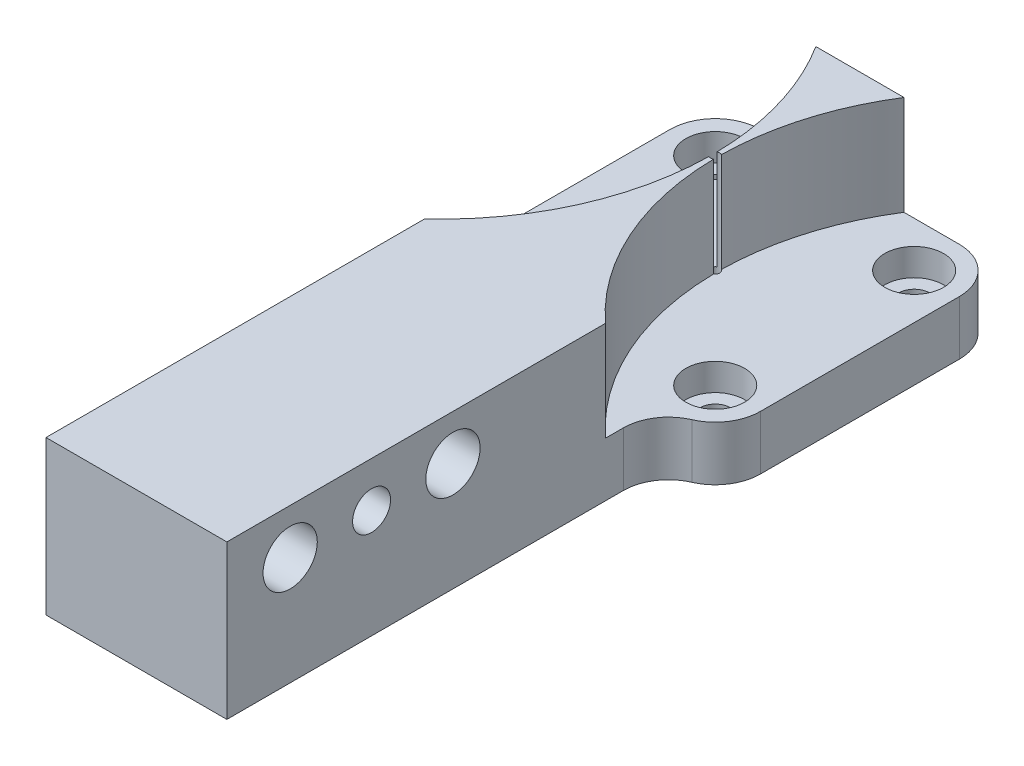
SolidWorks part; units mm, degrees
ref_plane "Front Plane" through (0, 0, 0) normal (0, 0, 1) x (1, 0, 0)
ref_plane "Top Plane" through (0, 0, 0) normal (0, 1, 0) x (1, 0, 0)
ref_plane "Right Plane" through (0, 0, 0) normal (1, 0, 0) x (0, 0, -1)
sketch "Sketch1" plane through (0, 0, 0) normal (0, 1, 0) x (1, 0, 0)
  line L0 (-16.25, 0) -> (16.25, 0)
  line L1 (-16.25, 0) -> (-16.25, -80.25)
  line L2 (-16.25, -80.25) -> (16.25, -80.25)
  line L3 (16.25, -80.25) -> (16.25, 0)
  line L4 (-0.45, -16.25) -> (-0.25, -16.25) construction
  line L5 (0.45, -16.25) -> (0.25, -16.25) construction
  line L6 (-16.25, -52.25) -> (16.25, -52.25) construction
  line L7 (11, -27.25) -> (-11, -27.25) construction
  line L8 (11, -27.25) -> (11, -5.25) construction
  line L9 (11, -5.25) -> (-11, -5.25) construction
  line L10 (-11, -27.25) -> (-11, -5.25) construction
  line L11 (11, -27.25) -> (-11, -5.25) construction
  line L12 (11, -5.25) -> (-11, -27.25) construction
  line L13 (-16.25, -58.25) -> (16.25, -58.25) construction
  line L14 (-16.25, -76.25) -> (16.25, -76.25) construction
  line L15 (-16.25, -70.25) -> (16.25, -70.25) construction
  line L16 (-16.25, -66.75) -> (16.25, -66.75) construction
  line L17 (-16.25, -61.75) -> (16.25, -61.75) construction
  line L18 (0, -52.25) -> (0, -58.25) construction
  line L19 (0, -66.75) -> (0, -61.75) construction
  line L20 (0, -70.25) -> (0, -76.25) construction
  line L21 (0, -58.25) -> (0, -66.75) construction
  line L22 (0, -61.75) -> (0, -70.25) construction
  line L23 (-16.25, -48.25) -> (16.25, -48.25) construction
  line L24 (0, -52.25) -> (0, -48.25) construction
  line L25 (0, -76.25) -> (0, -80.25) construction
  line L26 (0, -16.25) -> (0, 15.25) construction
  line L27 (-12.775, 15.25) -> (12.775, 15.25) construction
  line L28 (-30.25, -46.25) -> (-30.25, -48.25) construction
  arc A0 (-16.25, -42.783) -> (-5.0322, 0) centre (-30.25, -16.25) ccw construction
  circle A1 centre (0, -16.25) radius 0.45 construction
  arc A2 (5.0322, 0) -> (16.25, -42.783) centre (30.25, -16.25) ccw construction
  circle A3 centre (-11, -5.25) radius 5.25 construction
  circle A4 centre (-11, -5.25) radius 3.25 construction
  circle A5 centre (-11, -5.25) radius 1.5 construction
  arc A6 (-16.25, -42.783) -> (-5.0322, 0) centre (-30.25, -16.25) cw construction
  circle A7 centre (-12.775, 15.25) radius 5 construction
  circle A8 centre (12.775, 15.25) radius 5 construction
  point P43 (0, -55.25)
  point P44 (0, -73.25)
  dimension "D1" = 0.9
  dimension "D4" = 2
  dimension "D5" = 6.5
  dimension "D6" = 3
  dimension "D7" = 30
  dimension "D17" = 10
  dimension "D2" = 0.2
  dimension "D3" = 22
  dimension "D8" = 32.5
  dimension "D9" = 4
  dimension "D10" = 6
  dimension "D11" = 18
  dimension "D12" = 5
  dimension "D13" = 2
  dimension "D15" = 31.5
  dimension "D16" = 25.55
  dimension "D18" = 3.5
extrude "Boss-Extrude1" add sketch "Sketch1" against normal blind 6
sketch "Sketch2" plane through (0, 0, 0) normal (0, 1, 0) x (1, 0, 0)
  line L0 (-5.0322, 0) -> (5.0322, 0)
  line L1 (-16.25, -42.783) -> (-16.25, -80.25)
  line L2 (-16.25, -80.25) -> (16.25, -80.25)
  line L3 (16.25, -80.25) -> (16.25, -42.783)
  arc A0 (5.0322, 0) -> (16.25, -42.783) centre (30.25, -16.25) ccw construction
  arc A1 (-16.25, -42.783) -> (-5.0322, 0) centre (-30.25, -16.25) ccw construction
  arc A2 (5.0322, 0) -> (16.25, -42.783) centre (30.25, -16.25) ccw
  arc A3 (-16.25, -42.783) -> (-5.0322, 0) centre (-30.25, -16.25) ccw
extrude "Boss-Extrude2" add sketch "Sketch2" along normal blind 11
sketch "Sketch3" plane through (16.25, 0, 0) normal (1, 0, 0) x (0, 0, -1)
  line L0 (-73.25, 11) -> (-73.25, 1) construction
  line L1 (-80.25, 11) -> (-42.783, 11) construction
  line L3 (-55.25, 11) -> (-55.25, 1) construction
  line L4 (-64.25, 11) -> (-64.25, 1) construction
  line L6 (-80.25, 0) -> (0, 0) construction
  line L7 (-66.75, 0) -> (-61.75, 0) construction
  point P20 (-64.25, 0)
  dimension "D1" = 10
hole_wizard "Ø6.0mm Dowel Hole1" positions "Sketch4" profile "Sketch5" hole size "Ø6.0" standard "ANSI Metric" end condition through all
sketch "Sketch4" plane through (16.25, 0, 0) normal (1, 0, 0) x (0, 0, -1)
  line L0 (-73.25, 11) -> (-73.25, 1) construction
  line L1 (-55.25, 11) -> (-55.25, 1) construction
  point P0 (-73.25, 6)
  point P4 (-55.25, 6)
sketch "Sketch5" plane through (16.25, 6, 73.25) normal (0, 1, 0) x (0, 0, -1)
  line L0 (0, 0) -> (0, 32.5)
  line L1 (0, 32.5) -> (3, 32.5)
  line L2 (3, 32.5) -> (3, 0)
  line L5 (3, 0) -> (0, 0)
  line L11 (0, -6.35) -> (0, 107.95) construction
  dimension "Thru Hole Dia." = 6
  dimension "Thru Hole Depth" = 32.5
hole_wizard "M5x0.8 Tapped Hole1" positions "Sketch6" profile "Sketch7" tap size "M5x0.8" standard "ANSI Metric" end condition through all
sketch "Sketch6" plane through (16.25, 0, 0) normal (1, 0, 0) x (0, 0, -1)
  line L0 (-64.25, 11) -> (-64.25, 1) construction
  point P0 (-64.25, 6)
sketch "Sketch7" plane through (16.25, 6, 64.25) normal (0, 1, 0) x (0, 0, -1)
  line L0 (0, 0) -> (0, 32.5)
  line L1 (0, 32.5) -> (2.1, 32.5)
  line L2 (2.1, 32.5) -> (2.1, 0)
  line L5 (2.1, 0) -> (0, 0)
  line L11 (0, -6.35) -> (0, 107.95) construction
  dimension "Thru Tap Drill Dia." = 4.2
  dimension "Thru Tap Drill Depth" = 32.5
cosmetic thread "Hole Thread1" parameters "D2"=5
hole_wizard "CBORE for M3 SHCS1" positions "Sketch8" profile "Sketch9" counterbore size "M3" standard "ANSI Metric" end condition through all
sketch "Sketch8" plane through (0, 0, 0) normal (0, 1, 0) x (1, 0, 0)
  point P0 (-11, -5.25)
  point P3 (11, -5.25)
  point P6 (11, -27.25)
  point P9 (-11, -27.25)
sketch "Sketch9" plane through (-11, 0, 5.25) normal (1, 0, 0) x (0, 0, 1)
  line L0 (0, 0) -> (0, 6)
  line L1 (0, 6) -> (1.7, 6)
  line L3 (1.7, 6) -> (1.7, 3)
  line L4 (1.7, 3) -> (3.25, 3)
  line L5 (3.25, 3) -> (3.25, 0)
  line L7 (3.25, 0) -> (0, 0)
  line L11 (0, -6.35) -> (0, 107.95) construction
  dimension "Thru Hole Dia." = 3.4
  dimension "Thru Hole Depth" = 6
  dimension "C'Bore Dia." = 6.5
  dimension "C'Bore Depth" = 3
hole_wizard "Ø1.0 (1) Diameter Hole1" positions "Sketch10" profile "Sketch11" hole size "Ø1.0" standard "ANSI Metric" end condition through all
sketch "Sketch10" plane through (0, 11, 0) normal (0, 1, 0) x (1, 0, 0)
  point P0 (0, -16.25)
sketch "Sketch11" plane through (0, 11, 16.25) normal (1, 0, 0) x (0, 0, 1)
  line L0 (0, 0) -> (0, 17)
  line L1 (0, 17) -> (0.5, 17)
  line L2 (0.5, 17) -> (0.5, 0)
  line L5 (0.5, 0) -> (0, 0)
  line L11 (0, -6.35) -> (0, 107.95) construction
  dimension "Thru Hole Dia." = 1
  dimension "Thru Hole Depth" = 17
sketch "Sketch12" plane through (0, -6, 0) normal (0, -1, 0) x (1, 0, 0)
  circle A0 centre (0, 16.25) radius 1.5
  dimension "D1" = 3
extrude "Cut-Extrude1" cut sketch "Sketch12" against normal blind 5
sketch "Sketch13" plane through (0, 11, 0) normal (0, 1, 0) x (1, 0, 0)
  line L0 (-16.25, 0) -> (-16.25, -80.25) construction
  line L1 (-16.25, -45.25) -> (-10.25, -45.25)
  line L2 (-16.25, -45.25) -> (-16.25, -80.25)
  line L3 (-16.25, -80.25) -> (-10.25, -80.25)
  line L4 (-10.25, -45.25) -> (-10.25, -80.25)
  line L5 (-16.25, -80.25) -> (16.25, -80.25) construction
  line L6 (16.25, -80.25) -> (16.25, 0) construction
  line L7 (16.25, -45.25) -> (10.25, -45.25)
  line L8 (16.25, -45.25) -> (16.25, -80.25)
  line L9 (16.25, -80.25) -> (10.25, -80.25)
  line L10 (10.25, -45.25) -> (10.25, -80.25)
  line L11 (-16.25, -48.25) -> (16.25, -48.25) construction
  arc A0 (-16.25, -42.783) -> (-0.2531, -16.6812) centre (-30.25, -16.25) ccw construction
  point P16 (-30.25, -16.25)
  dimension "D1" = 3
  dimension "D2" = 20
extrude "Cut-Extrude2" cut sketch "Sketch13" against normal through all
fillet "Fillet1" radius 2.3813 2 edges at (10.25, 2.5, 45.25) (-10.25, 2.5, 45.25)
sketch "Sketch14" plane through (0, 11, 0) normal (0, 1, 0) x (1, 0, 0)
  line L0 (5.0322, 0) -> (-5.0322, 0) construction
  line L1 (-17.25, 1) -> (17.25, 1)
  line L2 (-17.25, 1) -> (-17.25, -81.25)
  line L3 (-17.25, -81.25) -> (17.25, -81.25)
  line L4 (17.25, 1) -> (17.25, -81.25)
  line L5 (-10, -80.25) -> (-10, -36.4152)
  line L6 (-10.25, -80.25) -> (10.25, -80.25) construction
  line L7 (-10, -80.25) -> (10, -80.25)
  line L8 (10, -80.25) -> (10, -36.4152)
  line L9 (-16, -5.25) -> (-16, -27.25)
  line L10 (-11, -0.25) -> (11, -0.25)
  line L11 (16, -5.25) -> (16, -27.25)
  arc A0 (-11, -0.25) -> (-16, -5.25) centre (-11, -5.25) ccw
  circle A2 centre (-16.25, 0) radius 1 construction
  circle A3 centre (-10.25, -80.25) radius 1 construction
  circle A4 centre (16.25, 0) radius 1 construction
  arc A5 (16, -5.25) -> (11, -0.25) centre (11, -5.25) ccw
  arc A6 (13, -31.8326) -> (16, -27.25) centre (11, -27.25) ccw
  arc A7 (-16, -27.25) -> (-13, -31.8326) centre (-11, -27.25) ccw
  arc A8 (-10, -36.4152) -> (-13, -31.8326) centre (-15, -36.4152) ccw
  arc A10 (13, -31.8326) -> (10, -36.4152) centre (15, -36.4152) ccw
  point P5 (-15.8745, -5.25)
  point P19 (-7.5749, -37.1252)
  dimension "D1" = 1
  dimension "D2" = 5
  dimension "D3" = 20
extrude "Cut-Extrude3" cut sketch "Sketch14" against normal through all
